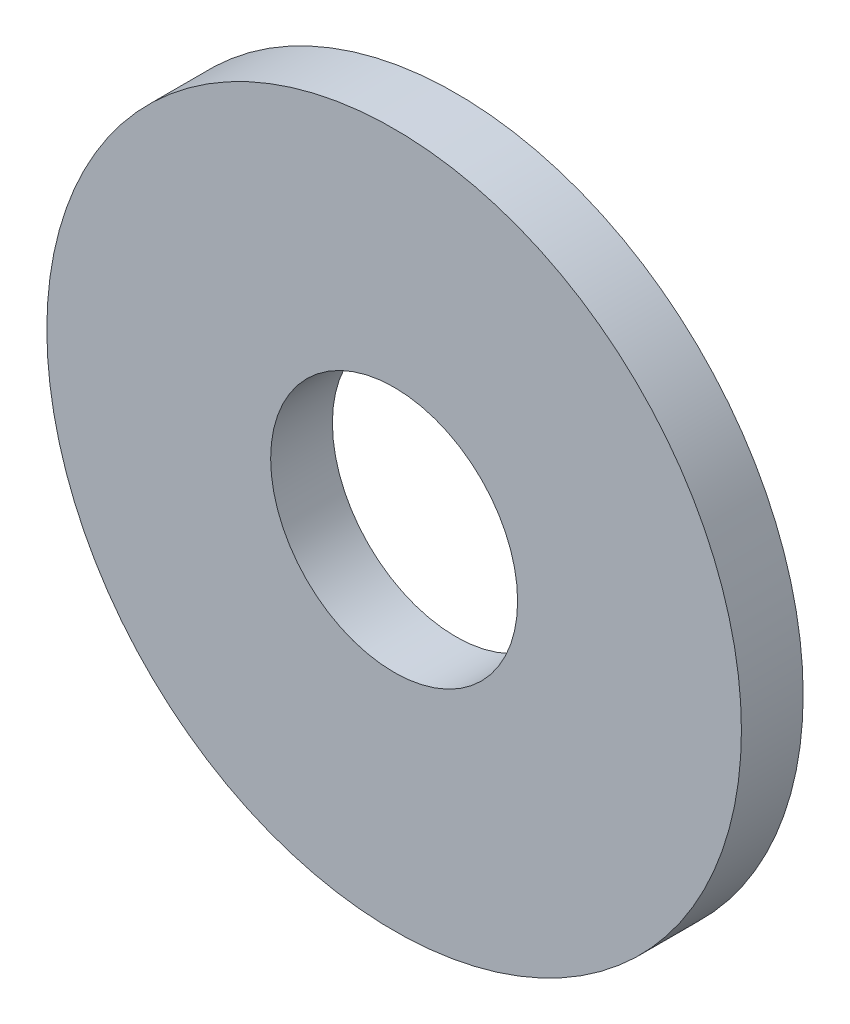
SolidWorks part; units mm, degrees
ref_plane "Спереди" through (0, 0, 0) normal (0, 0, 1) x (1, 0, 0)
ref_plane "Сверху" through (0, 0, 0) normal (0, 1, 0) x (1, 0, 0)
ref_plane "Справа" through (0, 0, 0) normal (1, 0, 0) x (0, 0, -1)
sketch "Эскиз1" plane through (0, 0, 0) normal (0, 0, 1) x (1, 0, 0)
  circle A0 centre (0, 0) radius 9
  circle A1 centre (0, 0) radius 3.2
  dimension "D1" = 6.4
  dimension "D2" = 18
extrude "Бобышка-Вытянуть1" add sketch "Эскиз1" along normal blind 1.6
